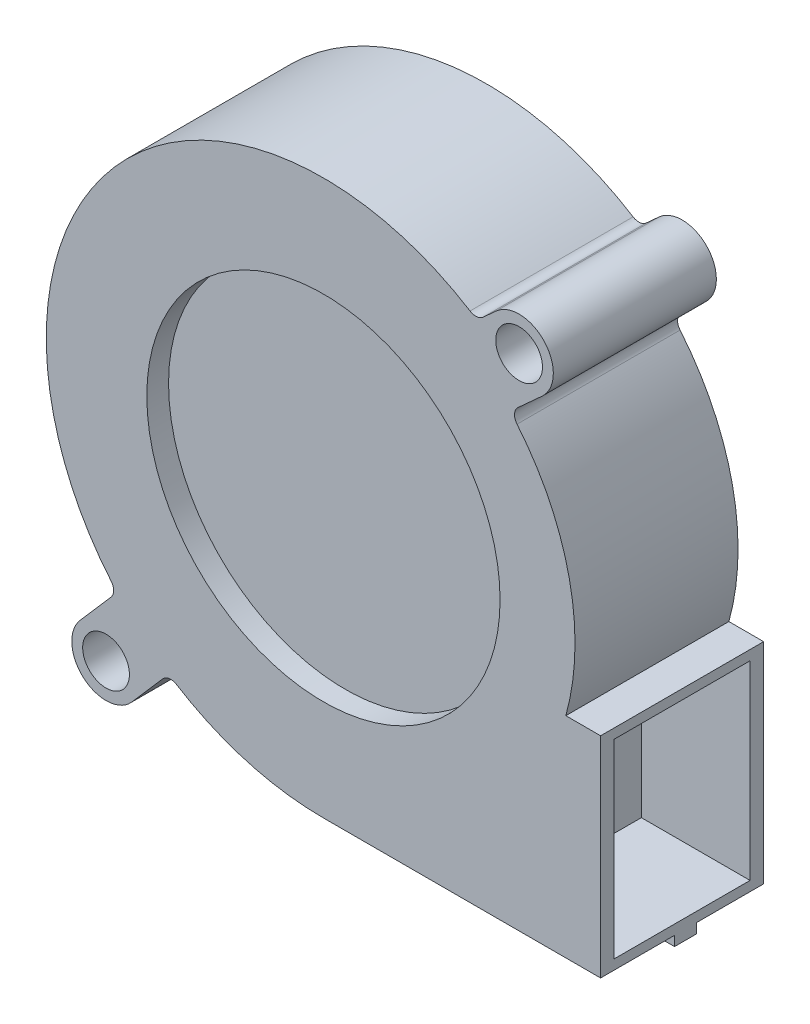
SolidWorks part; units mm, degrees
ref_plane "Front" through (0, 0, 0) normal (0, 0, 1) x (1, 0, 0)
ref_plane "Top" through (0, 0, 0) normal (0, 1, 0) x (1, 0, 0)
ref_plane "Right" through (0, 0, 0) normal (1, 0, 0) x (0, 0, -1)
sketch "Sketch1" plane through (0, 0, 0) normal (0, 0, 1) x (1, 0, 0)
  line L0 (0, 0) -> (-25.5, 0) construction
  line L1 (25.5, -25.5) -> (0, -25.5)
  line L2 (25.5, -25.5) -> (25.5, -6.2)
  line L3 (25.5, -6.2) -> (0, -6.2)
  line L4 (0, -25.5) -> (0, -6.2)
  line L5 (25.5, -25.5) -> (0, -6.2) construction
  line L6 (25.5, -6.2) -> (0, -25.5) construction
  line L7 (-17.623, -25.067) -> (-14.7972, -21.8173)
  line L8 (-14.2274, -21.162) -> (-18.9814, -17.0281) construction
  line L9 (-22.377, -20.933) -> (-19.5512, -17.6834)
  line L10 (15.8812, 22.8309) -> (14.6907, 21.7488)
  line L11 (14.1225, 21.2322) -> (18.9284, 17.087) construction
  line L12 (18.9284, 17.087) -> (20.1188, 18.1691)
  line L13 (18.9284, 17.087) -> (17.9083, 16.1597)
  arc A0 (-13.5127, -21.6254) -> (24.7348, -6.2) centre (0, 0) ccw
  circle A1 centre (18, 20.5) radius 2.15
  circle A2 centre (-20, -23) radius 2.15
  circle A3 centre (18, 20.5) radius 3.15
  circle A4 centre (-20, -23) radius 3.15
  arc A5 (-18.9814, -17.0281) -> (-14.2274, -21.162) centre (0, 0) ccw construction
  arc A6 (-14.7972, -21.8173) -> (-13.5127, -21.6254) centre (-14.0426, -22.4735) cw
  arc A7 (-19.5395, -16.3846) -> (-19.5512, -17.6834) centre (-20.3058, -17.0272) cw
  arc A8 (13.4891, 21.6401) -> (-19.5395, -16.3846) centre (0, 0) ccw
  arc A9 (14.858, 20.7241) -> (14.1225, 21.2322) centre (0, 0) ccw construction
  arc A10 (18.6286, 17.4134) -> (14.858, 20.7241) centre (0, 0) ccw construction
  arc A11 (18.9284, 17.087) -> (18.6286, 17.4134) centre (0, 0) ccw construction
  arc A12 (17.1864, 15.5035) -> (-23.1458, 0) centre (0, 0) ccw construction
  arc A13 (22.3, -6.2) -> (17.8115, 14.7811) centre (0, 0) ccw
  arc A14 (-23.1458, 0) -> (21.089, -9.5385) centre (0, 0) ccw construction
  arc A15 (21.089, -9.5385) -> (22.3, -6.2) centre (0, 0) ccw construction
  arc A16 (24.7348, -6.2) -> (18.9284, 17.087) centre (0, 0) ccw construction
  arc A17 (17.8115, 14.7811) -> (17.9083, 16.1597) centre (18.581, 15.4198) cw
  arc A18 (14.6907, 21.7488) -> (13.4891, 21.6401) centre (14.0181, 22.4887) cw
  point P7 (12.75, -15.85)
  point P29 (22.3, -6.2)
  dimension "D1" = 51
  dimension "D6" = 4.3
  dimension "D9" = 1
  dimension "D10" = 1
  dimension "D11" = 1
  dimension "D2" = 51
  dimension "D3" = 19.3
  dimension "D4" = 18
  dimension "D5" = 20.5
  dimension "D7" = 23
  dimension "D8" = 20
  dimension "D12" = 3.2
extrude "Boss-Extrude1" add sketch "Sketch1" along normal mid plane 15
sketch "Sketch3" plane through (25.5, 0, 0) normal (1, 0, 0) x (0, 0, -1)
  line L0 (-7.5, -25.5) -> (7.5, -25.5) construction
  line L1 (-0.7, -25.5) -> (1.3, -25.5)
  line L2 (-0.7, -25.5) -> (-0.7, -26.4)
  line L3 (-0.7, -26.4) -> (1.3, -26.4)
  line L4 (1.3, -25.5) -> (1.3, -26.4)
  line L5 (-0.7, -25.5) -> (1.3, -26.4) construction
  line L6 (-0.7, -26.4) -> (1.3, -25.5) construction
  point P4 (0.3, -25.95)
  dimension "D1" = 0.9
  dimension "D2" = 8.2
  dimension "D3" = 8.8
extrude "Boss-Extrude2" add sketch "Sketch3" against normal blind 11.4
sketch "Sketch4" plane through (0, 0, 7.5) normal (0, 0, 1) x (1, 0, 0)
  circle A0 centre (0, 0) radius 16.25
  dimension "D1" = 32.5
extrude "Cut-Extrude1" cut sketch "Sketch4" against normal blind 2
sketch "Sketch5" plane through (25.5, 0, 0) normal (1, 0, 0) x (0, 0, -1)
  line L0 (-7.5, -25.5) -> (-7.5, -6.2) construction
  line L1 (-6.25, -7.1) -> (6.25, -7.1)
  line L2 (-6.25, -7.1) -> (-6.25, -24.6)
  line L3 (-6.25, -24.6) -> (6.25, -24.6)
  line L4 (6.25, -7.1) -> (6.25, -24.6)
  line L5 (-6.25, -7.1) -> (6.25, -24.6) construction
  line L6 (-6.25, -24.6) -> (6.25, -7.1) construction
  point P4 (0, -15.85)
  point P9 (-7.5, -15.85)
  dimension "D1" = 12.5
  dimension "D2" = 17.5
extrude "Cut-Extrude2" cut sketch "Sketch5" against normal blind 10
